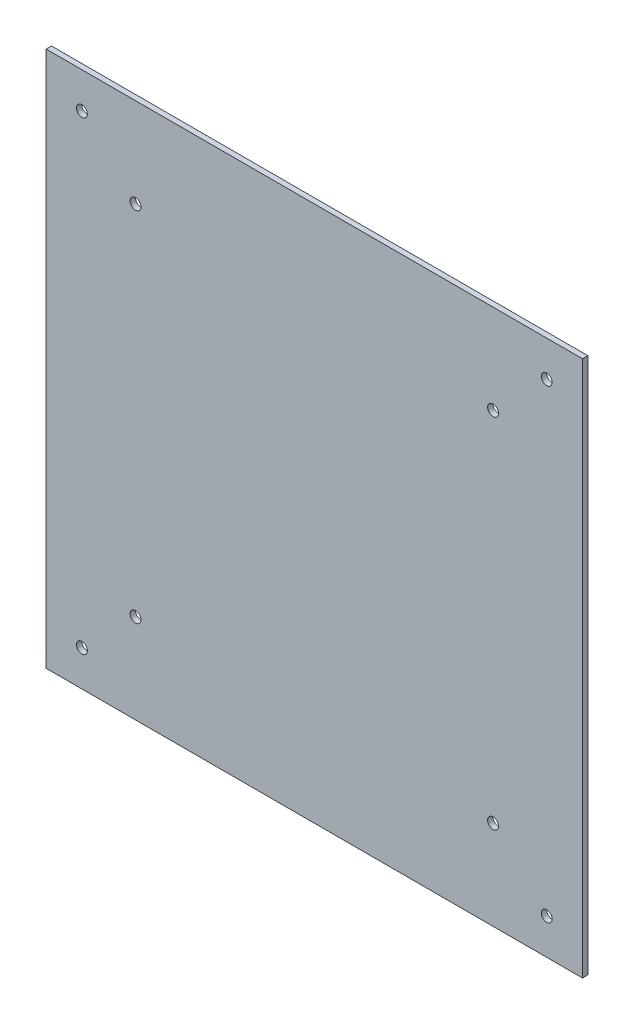
SolidWorks part; units mm, degrees
ref_plane "Front Plane" through (0, 0, 0) normal (0, 0, 1) x (1, 0, 0)
ref_plane "Top Plane" through (0, 0, 0) normal (0, 1, 0) x (1, 0, 0)
ref_plane "Right Plane" through (0, 0, 0) normal (1, 0, 0) x (0, 0, -1)
sketch "Sketch1" plane through (0, 0, 0) normal (0, 0, 1) x (1, 0, 0)
  line L1 (-150, 150) -> (150, 150)
  line L2 (-150, 150) -> (-150, -150)
  line L3 (-150, -150) -> (150, -150)
  line L4 (150, 150) -> (150, -150)
  line L5 (-150, 150) -> (150, -150) construction
  line L6 (-150, -150) -> (150, 150) construction
  point P0 (0, 0)
  dimension "D1" = 300
  dimension "D2" = 300
extrude "Boss-Extrude1" add sketch "Sketch1" along normal blind 3
sketch "Sketch3" plane through (0, 0, 3) normal (0, 0, 1) x (1, 0, 0)
  line L0 (-150, -150) -> (150, 150)
  line L1 (-150, 150) -> (150, -150)
hole_wizard "Ø6.1 (6.1) Diameter Hole1" positions "Sketch4" profile "Sketch5" hole size "Ø6.1" standard "ISO"
sketch "Sketch4" plane through (0, 0, 3) normal (0, 0, 1) x (1, 0, 0)
  line L0 (-150, -150) -> (150, 150) construction
  line L1 (-150, 150) -> (150, -150) construction
  point P0 (-130, -130)
  point P5 (-100, -100)
  point P7 (130, -130)
  point P11 (100, -100)
  point P15 (130, 130)
  point P17 (-100, 100)
  point P19 (-130, 130)
  point P21 (100, 100)
  dimension "D1" = 130
  dimension "D2" = 100
  dimension "D3" = 130
  dimension "D4" = 100
  dimension "D5" = 100
  dimension "D6" = 130
  dimension "D7" = 100
  dimension "D8" = 130
sketch "Sketch5" plane through (-130, -130, 3) normal (1, 0, 0) x (0, -1, 0)
  line L0 (0, 0) -> (0, 24.8326)
  line L1 (0, 24.8326) -> (3.05, 23)
  line L2 (3.05, 23) -> (3.05, 0)
  line L5 (3.05, 0) -> (0, 0)
  line L10 (0, 24.8326) -> (-3.05, 23) construction
  line L11 (0, -6.35) -> (0, 107.95) construction
  dimension "Hole Dia." = 6.1
  dimension "Hole Depth" = 23
  dimension "Drill Angle" = 118
